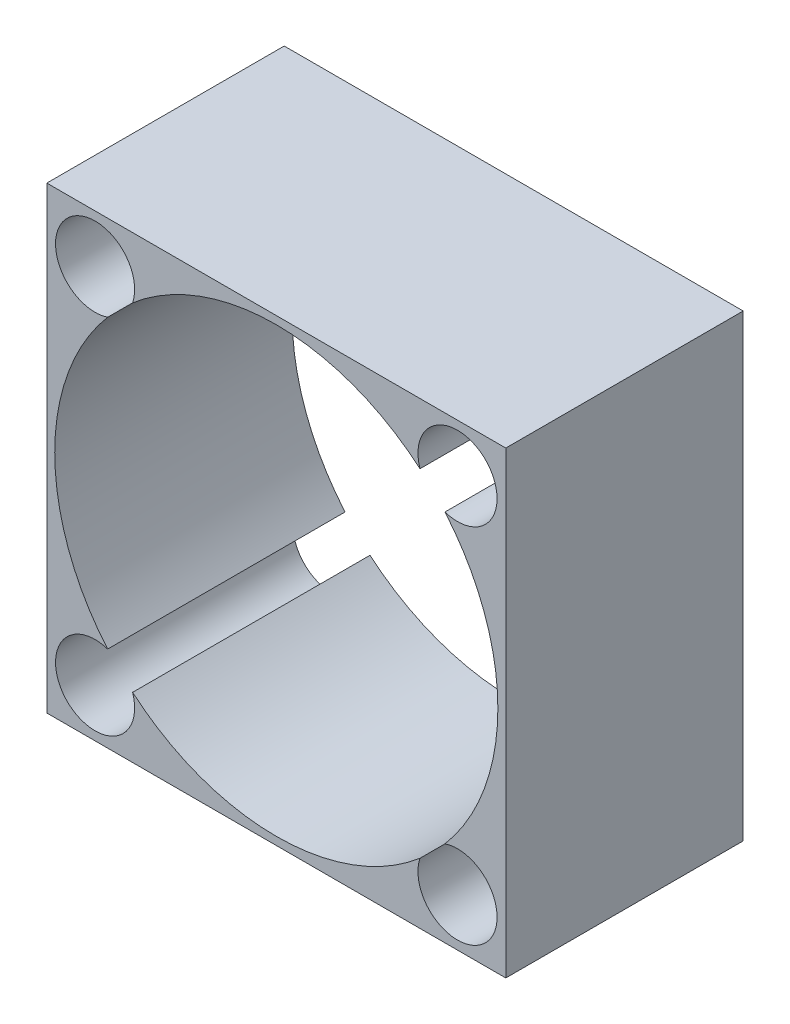
SolidWorks part; units mm, degrees
ref_plane "前视基准面" through (0, 0, 0) normal (0, 0, 1) x (1, 0, 0)
ref_plane "上视基准面" through (0, 0, 0) normal (0, 1, 0) x (1, 0, 0)
ref_plane "右视基准面" through (0, 0, 0) normal (1, 0, 0) x (0, 0, -1)
other "Configuration Table"
sketch "草图1" plane through (0, 0, 0) normal (0, 0, 1) x (1, 0, 0)
  line L1 (-29, 29) -> (29, 29)
  line L2 (-29, 29) -> (-29, -29)
  line L3 (-29, -29) -> (29, -29)
  line L4 (29, 29) -> (29, -29)
  line L5 (-29, 29) -> (29, -29) construction
  line L6 (-29, -29) -> (29, 29) construction
  circle A0 centre (0, 0) radius 28
  point P0 (0, 0)
extrude "凸台-拉伸1" add sketch "草图1" along normal blind 30
sketch "草图2" plane through (0, 0, 30) normal (0, 0, 1) x (1, 0, 0)
  line L0 (29, 29) -> (-29, -29) construction
  line L1 (-29, 29) -> (29, -29) construction
  line L2 (5.5691, 34.0289) -> (34.0289, 5.5691) construction
  line L3 (-29.7781, 9.8198) -> (-9.8198, 29.7781) construction
  line L4 (-33.1352, -6.4627) -> (-6.4627, -33.1352) construction
  line L5 (5.893, -33.705) -> (33.705, -5.893) construction
  line L16 (-22.9, 22.9) -> (22.9, -22.9) construction
  line L17 (-22.9, -22.9) -> (22.9, 22.9) construction
  circle A0 centre (22.9, 22.9) radius 5
  circle A1 centre (22.9, -22.9) radius 5
  circle A2 centre (-22.9, -22.9) radius 5
  circle A3 centre (-22.9, 22.9) radius 5
  point P8 (0, 0)
  point P11 (19.799, 19.799)
  point P14 (-19.799, 19.799)
  point P19 (-19.799, -19.799)
  point P20 (19.799, -19.799)
  point P21 (0, 0)
  point P22 (0, 0)
  point P29 (-23.0491, 23.0491)
  point P30 (0, 0)
  point P38 (22.9646, 22.9)
extrude "切除-拉伸1" cut sketch "草图2" against normal through all
